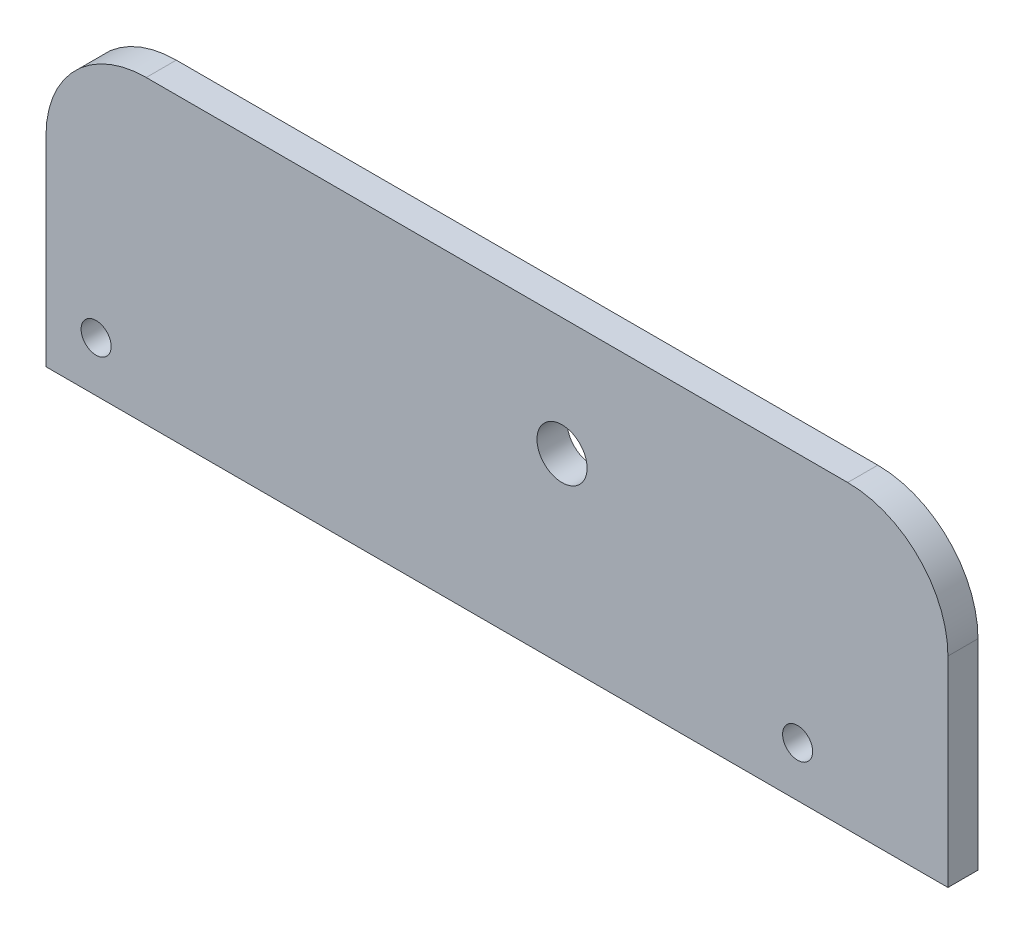
SolidWorks part; units mm, degrees
ref_plane "前视基准面" through (0, 0, 0) normal (0, 0, 1) x (1, 0, 0)
ref_plane "上视基准面" through (0, 0, 0) normal (0, 1, 0) x (1, 0, 0)
ref_plane "右视基准面" through (0, 0, 0) normal (1, 0, 0) x (0, 0, -1)
sketch "草图1" plane through (0, 0, 0) normal (0, 0, 1) x (1, 0, 0)
  line L1 (-45, 15) -> (45, 15)
  line L2 (-45, 15) -> (-45, -15)
  line L3 (-45, -15) -> (45, -15)
  line L4 (45, 15) -> (45, -15)
  line L5 (-45, 15) -> (45, -15) construction
  line L6 (-45, -15) -> (45, 15) construction
  point P0 (0, 0)
  dimension "D1" = 90
  dimension "D2" = 30
extrude "凸台-拉伸1" add sketch "草图1" along normal blind 3
sketch "草图3" plane through (0, 0, 3) normal (0, 0, 1) x (1, 0, 0)
  circle A1 centre (6.4923, 3.237) radius 2.5
  dimension "D1" = 5
extrude "切除-拉伸2" cut sketch "草图3" against normal blind 10
sketch "草图4" plane through (0, 0, 3) normal (0, 0, 1) x (1, 0, 0)
  circle A2 centre (-40, -10) radius 1.5 construction
  circle A3 centre (30, -10) radius 1.5 construction
  circle A4 centre (-40, -10) radius 1.5
  circle A5 centre (30, -10) radius 1.5
extrude "切除-拉伸3" cut sketch "草图4" against normal blind 10
fillet "圆角1" radius 10 2 edges at (-45, 15, 1.5) (45, 15, 1.5)
